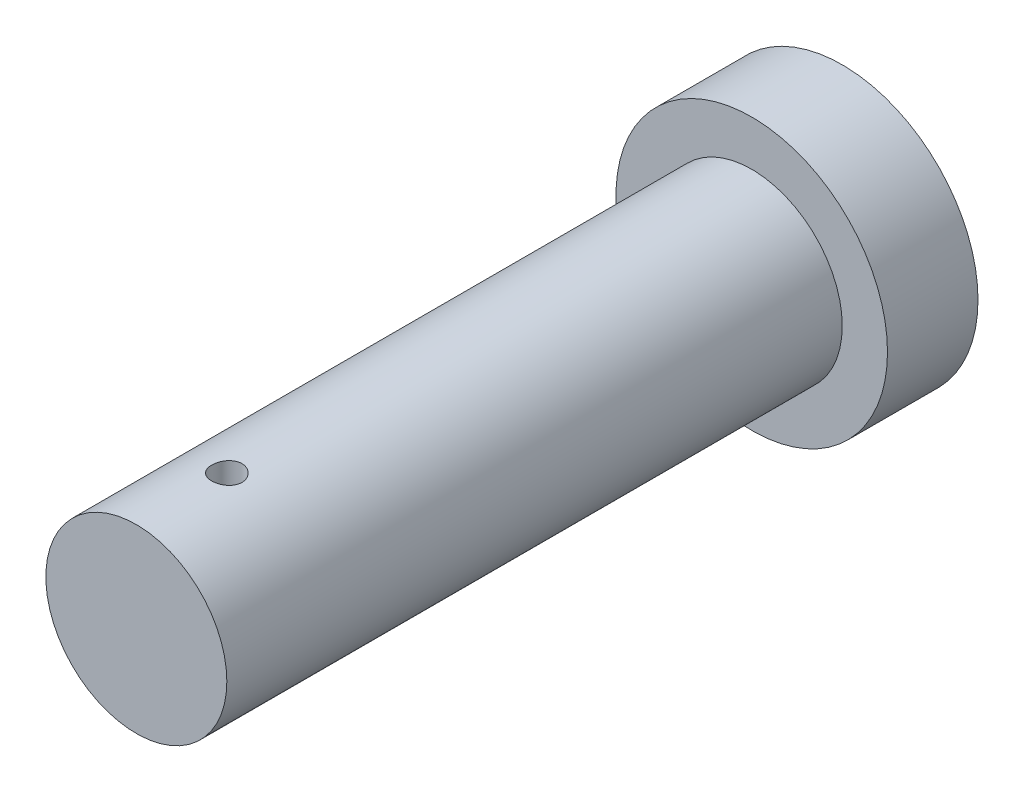
SolidWorks part; units mm, degrees
ref_plane "Front Plane" through (0, 0, 0) normal (0, 0, 1) x (1, 0, 0)
ref_plane "Top Plane" through (0, 0, 0) normal (0, 1, 0) x (1, 0, 0)
ref_plane "Right Plane" through (0, 0, 0) normal (1, 0, 0) x (0, 0, -1)
sketch "Sketch1" plane through (0, 0, 0) normal (0, 0, 1) x (1, 0, 0)
  circle A0 centre (0, 0) radius 22.5
extrude "Boss-Extrude1" add sketch "Sketch1" along normal blind 15
sketch "Sketch2" plane through (0, 0, 15) normal (0, 0, 1) x (1, 0, 0)
  circle A0 centre (0, 0) radius 15
extrude "Boss-Extrude2" add sketch "Sketch2" along normal blind 102
sketch "Sketch3" plane through (0, 0, 0) normal (0, 1, 0) x (1, 0, 0)
  line L0 (0, -117) -> (0, -102)
  line L1 (-15, -117) -> (15, -117) construction
  circle A0 centre (0, -102) radius 2.5
  point P6 (0, 0)
  dimension "D2" = 5
  dimension "D1" = 15
extrude "Cut-Extrude1" cut sketch "Sketch3" against normal mid plane 102 contours A0
